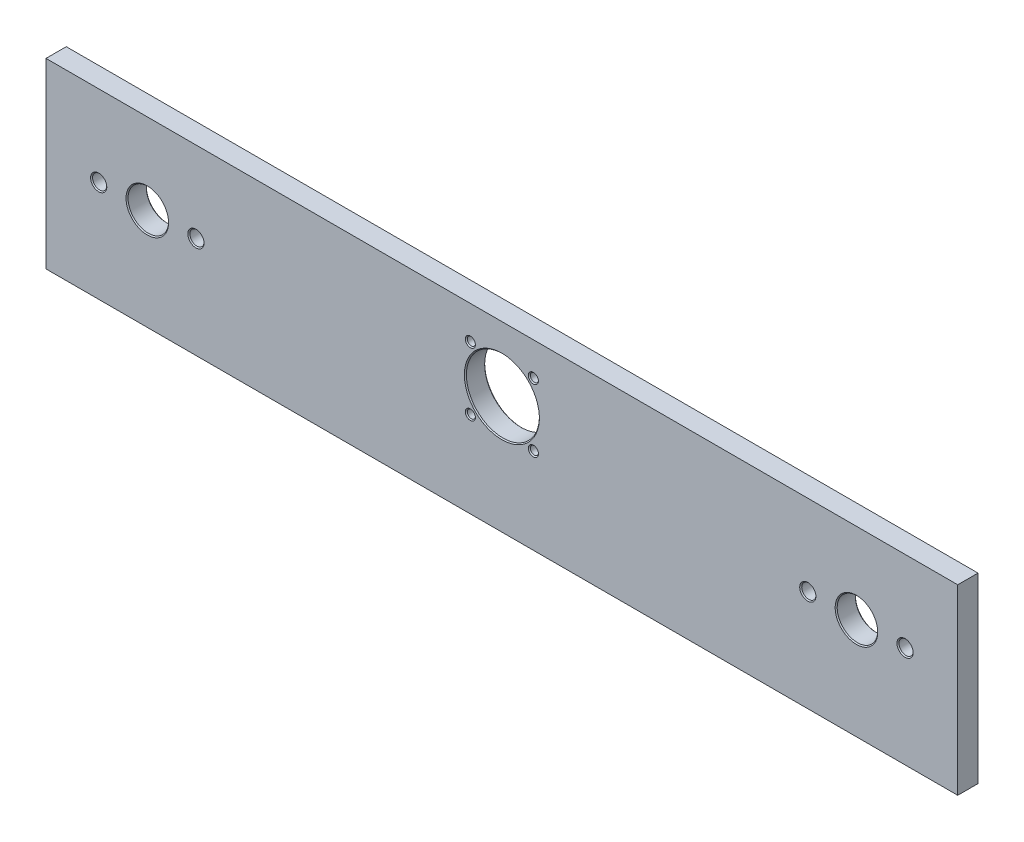
SolidWorks part; units mm, degrees
ref_plane "Alzado" through (0, 0, 0) normal (0, 0, 1) x (1, 0, 0)
ref_plane "Planta" through (0, 0, 0) normal (0, 1, 0) x (1, 0, 0)
ref_plane "Vista lateral" through (0, 0, 0) normal (1, 0, 0) x (0, 0, -1)
sketch "Croquis2" plane through (0, 0, 0) normal (0, 0, 1) x (1, 0, 0)
  line L1 (0, 0) -> (450, 0)
  line L2 (0, 0) -> (0, 90)
  line L3 (0, 90) -> (450, 90)
  line L4 (450, 0) -> (450, 90)
  dimension "D1" = 450
  dimension "D2" = 90
extrude "Saliente-Extruir1" add sketch "Croquis2" along normal blind 10
sketch "Croquis6" plane through (0, 0, 10) normal (0, 0, 1) x (1, 0, 0)
  line L0 (225, 90) -> (225, 0) construction
  line L1 (450, 90) -> (0, 90) construction
  line L2 (0, 0) -> (450, 0) construction
  line L3 (0, 58) -> (450, 58) construction
  line L4 (0, 90) -> (0, 0) construction
  line L5 (450, 0) -> (450, 90) construction
  circle A0 centre (225, 58) radius 18
  circle A1 centre (209.4378, 73.5505) radius 2
  circle A2 centre (240.5505, 73.5622) radius 2
  circle A3 centre (240.5622, 42.4495) radius 2
  circle A4 centre (209.4495, 42.4378) radius 2
  point P25 (225, 58)
  dimension "D2" = 36
  dimension "D3" = 4
  dimension "D4" = 4
  dimension "D6" = 22
  dimension "D5" = 22
  dimension "D7" = 22
  dimension "D1" = 32
extrude "Cortar-Extruir1" cut sketch "Croquis6" against normal through all
chamfer "Chaflán5" distance 0.5 angle 45 10 edges at (243, 58, 10) (243, 58, 0) (211.4495, 42.4378, 0) (242.5622, 42.4495, 0) (211.4378, 73.5505, 0) (242.5505, 73.5622, 0) (242.5622, 42.4495, 10) (211.4495, 42.4378, 10) (242.5505, 73.5622, 10) (211.4378, 73.5505, 10)
sketch "Croquis9" plane through (0, 0, 10) normal (0, 0, 1) x (1, 0, 0)
  line L0 (0, 50) -> (450, 50) construction
  line L1 (0, 90) -> (0, 0) construction
  line L2 (450, 0) -> (450, 90) construction
  line L3 (225, 90) -> (225, 0) construction
  line L4 (450, 90) -> (0, 90) construction
  line L5 (0, 0) -> (450, 0) construction
  circle A0 centre (50, 50) radius 10
  circle A1 centre (400, 50) radius 10
  circle A2 centre (26, 50) radius 3.5
  circle A3 centre (74, 50) radius 3.5
  circle A4 centre (376, 50) radius 3.5
  circle A5 centre (424, 50) radius 3.5
  circle A6 centre (225, 58) radius 18.5 construction
  dimension "D1" = 20
  dimension "D2" = 350
  dimension "D5" = 7
  dimension "D6" = 24
  dimension "D7" = 24
  dimension "D4" = 175
  dimension "D3" = 40
extrude "Cortar-Extruir2" cut sketch "Croquis9" against normal through all
chamfer "Chaflán6" distance 0.5 angle 45 12 edges at (60, 50, 10) (60, 50, 0) (390, 50, 10) (390, 50, 0) (29.5, 50, 0) (77.5, 50, 0) (372.5, 50, 0) (420.5, 50, 0) (420.5, 50, 10) (372.5, 50, 10) (77.5, 50, 10) (29.5, 50, 10)
